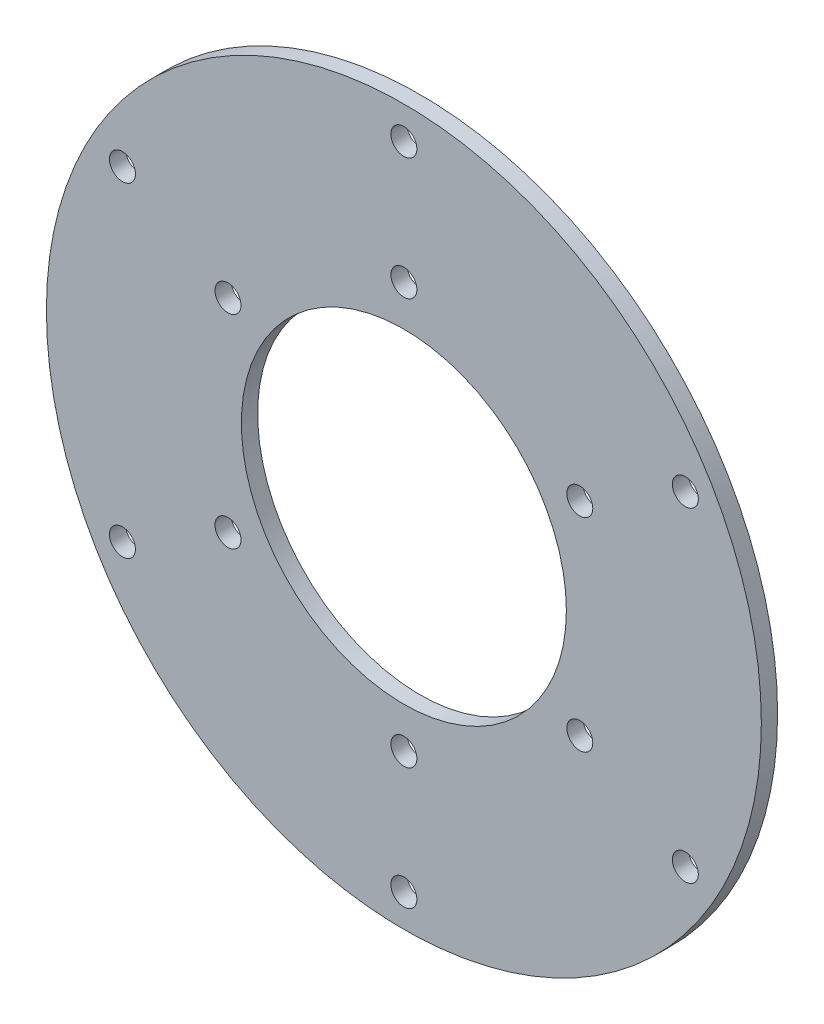
SolidWorks part; units mm, degrees
material "Thornel Mat VMA"
ref_plane "前视基准面" through (0, 0, 0) normal (0, 0, 1) x (1, 0, 0)
ref_plane "上视基准面" through (0, 0, 0) normal (0, 1, 0) x (1, 0, 0)
ref_plane "右视基准面" through (0, 0, 0) normal (1, 0, 0) x (0, 0, -1)
sketch "草图1" plane through (0, 0, 0) normal (0, 0, 1) x (1, 0, 0)
  circle A0 centre (0, 0) radius 44
  circle A1 centre (0, 0) radius 40 construction
  circle A2 centre (0, 40) radius 1.6
  circle A3 centre (34.641, 20) radius 1.6
  circle A4 centre (34.641, -20) radius 1.6
  circle A5 centre (0, -40) radius 1.6
  circle A6 centre (-34.641, -20) radius 1.6
  circle A7 centre (-34.641, 20) radius 1.6
  circle A8 centre (0, 0) radius 25 construction
  circle A9 centre (0, 25) radius 1.6
  circle A10 centre (21.6506, 12.5) radius 1.6
  circle A11 centre (21.6506, -12.5) radius 1.6
  circle A12 centre (0, -25) radius 1.6
  circle A13 centre (-21.6506, -12.5) radius 1.6
  circle A14 centre (-21.6506, 12.5) radius 1.6
  circle A15 centre (0, 0) radius 20
  point P19 (0, 0)
  point P33 (0, 0)
  dimension "D1" = 88
  dimension "D2" = 80
  dimension "D3" = 3.2
  dimension "D5" = 50
  dimension "D6" = 3.2
  dimension "D8" = 40
  dimension "D4" = 6
  dimension "D7" = 6
extrude "凸台-拉伸1" add sketch "草图1" along normal blind 2
